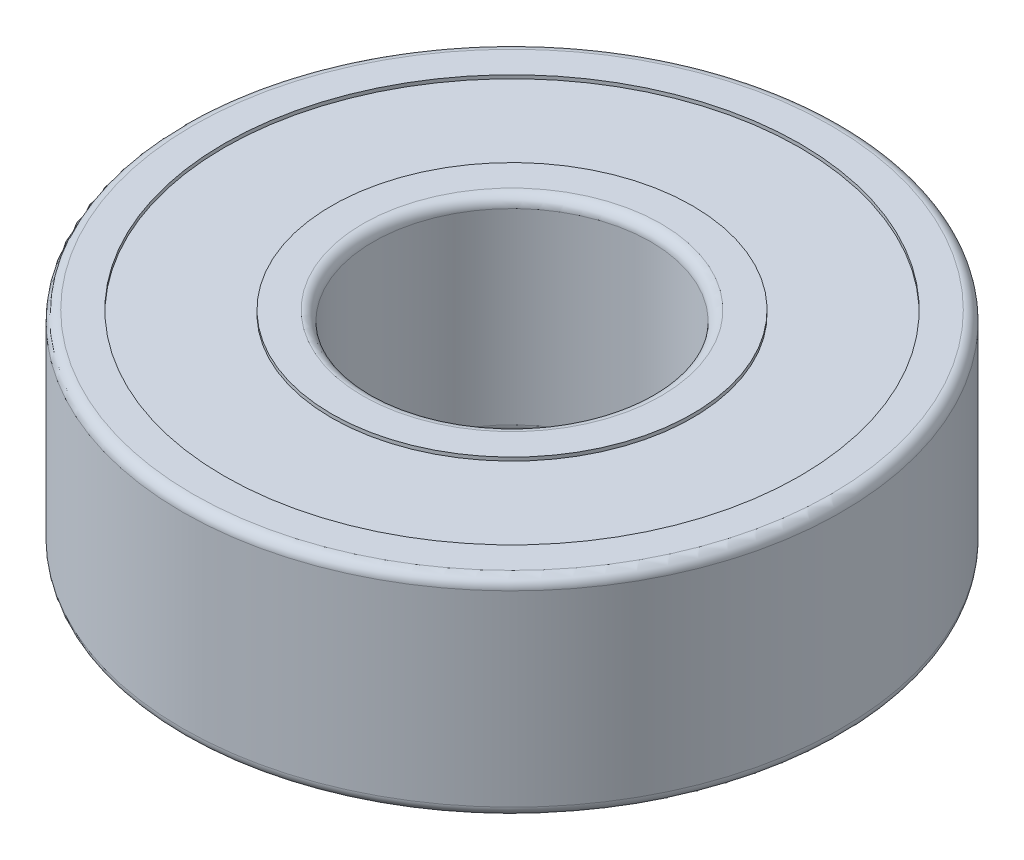
SolidWorks part; units mm, degrees
ref_plane "Alzado" through (0, 0, 0) normal (0, 0, 1) x (1, 0, 0)
ref_plane "Planta" through (0, 0, 0) normal (0, 1, 0) x (1, 0, 0)
ref_plane "Vista lateral" through (0, 0, 0) normal (1, 0, 0) x (0, 0, -1)
sketch "Croquis1" plane through (0, 0, 0) normal (0, 1, 0) x (1, 0, 0)
  circle A0 centre (0, 0) radius 4
  circle A1 centre (0, 0) radius 9.5
  dimension "D1" = 19
  dimension "D2" = 8
extrude "Saliente-Extruir1" add sketch "Croquis1" along normal blind 6
sketch "Croquis2" plane through (0, 6, 0) normal (0, 1, 0) x (1, 0, 0)
  circle A0 centre (0, 0) radius 8.3
  circle A1 centre (0, 0) radius 5.2
  circle A2 centre (0, 0) radius 4 construction
  circle A3 centre (0, 0) radius 9.5 construction
  dimension "D1" = 1.2
  dimension "D2" = 1.2
extrude "Cortar-Extruir1" cut sketch "Croquis2" against normal blind 0.1
ref_plane "Plano1" through (0, 3, 0) normal (0, 1, 0) x (1, 0, 0)
mirror "Simetría1" about plane through (0, 3, 0) normal (0, 1, 0) of "Cortar-Extruir1"
fillet "Redondeo1" radius 0.3 4 edges at (0, 0, 9.5) (0, 6, 9.5) (0, 0, 4) (0, 6, 4)
